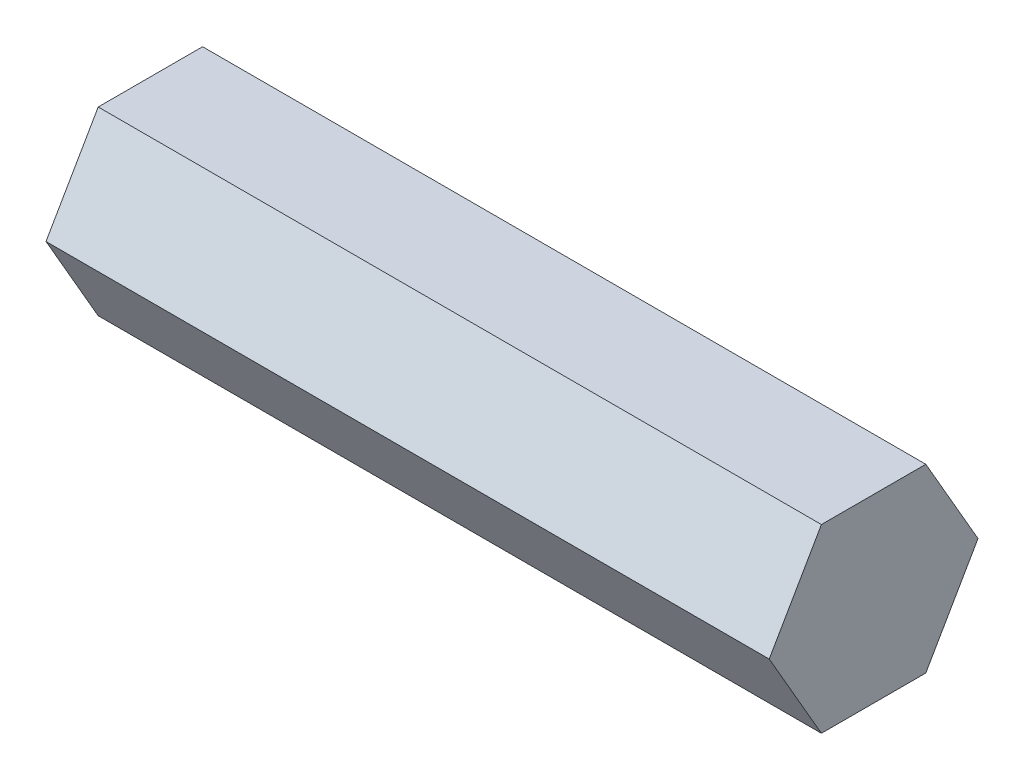
SolidWorks part; units mm, degrees
ref_plane "Front Plane" through (0, 0, 0) normal (0, 0, 1) x (1, 0, 0)
ref_plane "Top Plane" through (0, 0, 0) normal (0, 1, 0) x (1, 0, 0)
ref_plane "Right Plane" through (0, 0, 0) normal (1, 0, 0) x (0, 0, -1)
sketch "Sketch1" plane through (0, 0, 0) normal (1, 0, 0) x (0, 0, -1)
  line L1 (7.3323, 0) -> (3.6662, 6.35)
  line L2 (3.6662, 6.35) -> (-3.6662, 6.35)
  line L3 (-3.6662, 6.35) -> (-7.3323, 0)
  line L4 (-7.3323, 0) -> (-3.6662, -6.35)
  line L5 (-3.6662, -6.35) -> (3.6662, -6.35)
  line L6 (3.6662, -6.35) -> (7.3323, 0)
  circle A0 centre (0, 0) radius 6.35 construction
  dimension "D1" = 12.7
extrude "Boss-Extrude1" add sketch "Sketch1" along normal mid plane 50.8
sketch "Sketch2" plane through (-25.4, 0, 0) normal (-1, 0, 0) x (0, 0, 1)
  line L1 (3.4641, 0) -> (1.7321, 3)
  line L2 (1.7321, 3) -> (-1.7321, 3)
  line L3 (-1.7321, 3) -> (-3.4641, 0)
  line L4 (-3.4641, 0) -> (-1.7321, -3)
  line L5 (-1.7321, -3) -> (1.7321, -3)
  line L6 (1.7321, -3) -> (3.4641, 0)
  circle A0 centre (0, 0) radius 3 construction
  dimension "D1" = 6
extrude "Cut-Extrude1" cut sketch "Sketch2" against normal blind 12.7
equation "\"D1@Sketch2\"=6mm"
